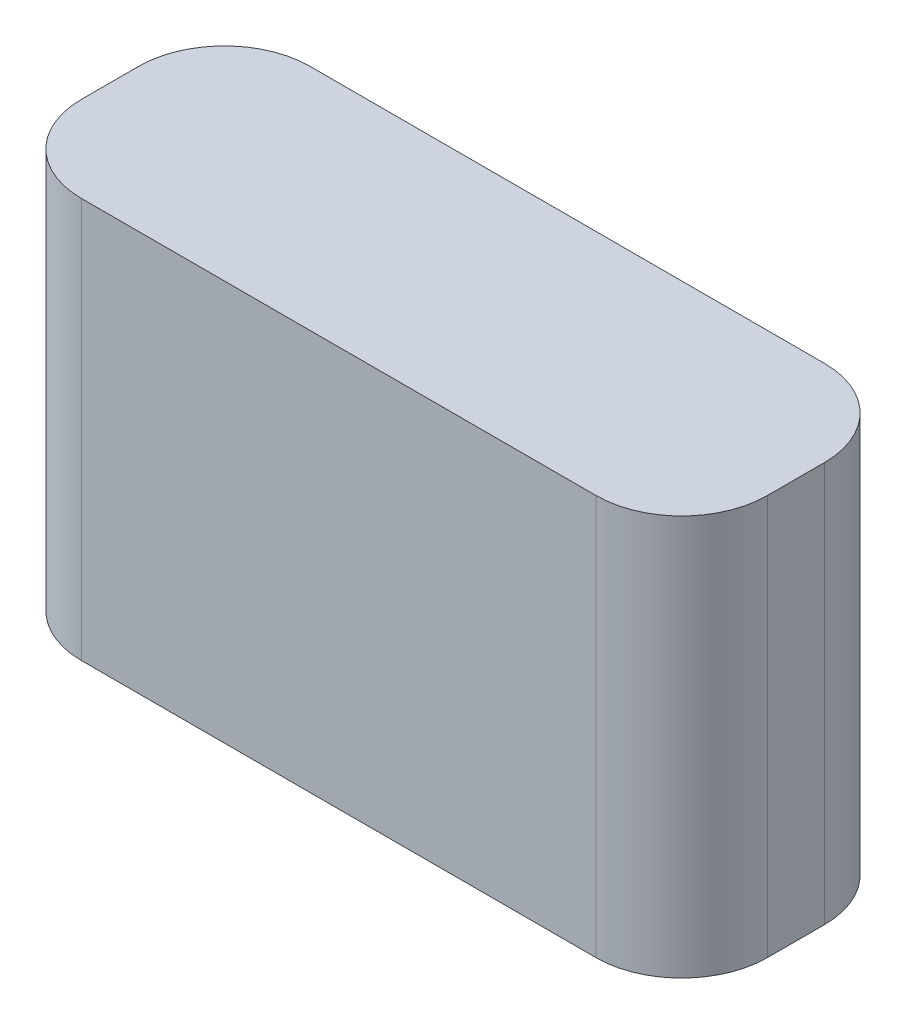
SolidWorks part; units mm, degrees
ref_plane "Front Plane" through (0, 0, 0) normal (0, 0, 1) x (1, 0, 0)
ref_plane "Top Plane" through (0, 0, 0) normal (0, 1, 0) x (1, 0, 0)
ref_plane "Right Plane" through (0, 0, 0) normal (1, 0, 0) x (0, 0, -1)
sketch "Sketch1" plane through (0, 0, 0) normal (0, 1, 0) x (1, 0, 0)
  line L1 (-45, -20) -> (45, -20)
  line L2 (-60, -5) -> (-60, 5)
  line L3 (-45, 20) -> (45, 20)
  line L4 (60, -5) -> (60, 5)
  line L5 (-60, -20) -> (60, 20) construction
  line L6 (-60, 20) -> (60, -20) construction
  arc A0 (45, 20) -> (60, 5) centre (45, 5) cw
  arc A1 (45, -20) -> (60, -5) centre (45, -5) ccw
  arc A2 (-45, -20) -> (-60, -5) centre (-45, -5) cw
  arc A3 (-60, 5) -> (-45, 20) centre (-45, 5) cw
  point P0 (0, 0)
  dimension "D3" = 15
  dimension "D1" = 120
  dimension "D2" = 40
extrude "Boss-Extrude1" add sketch "Sketch1" along normal blind 70
